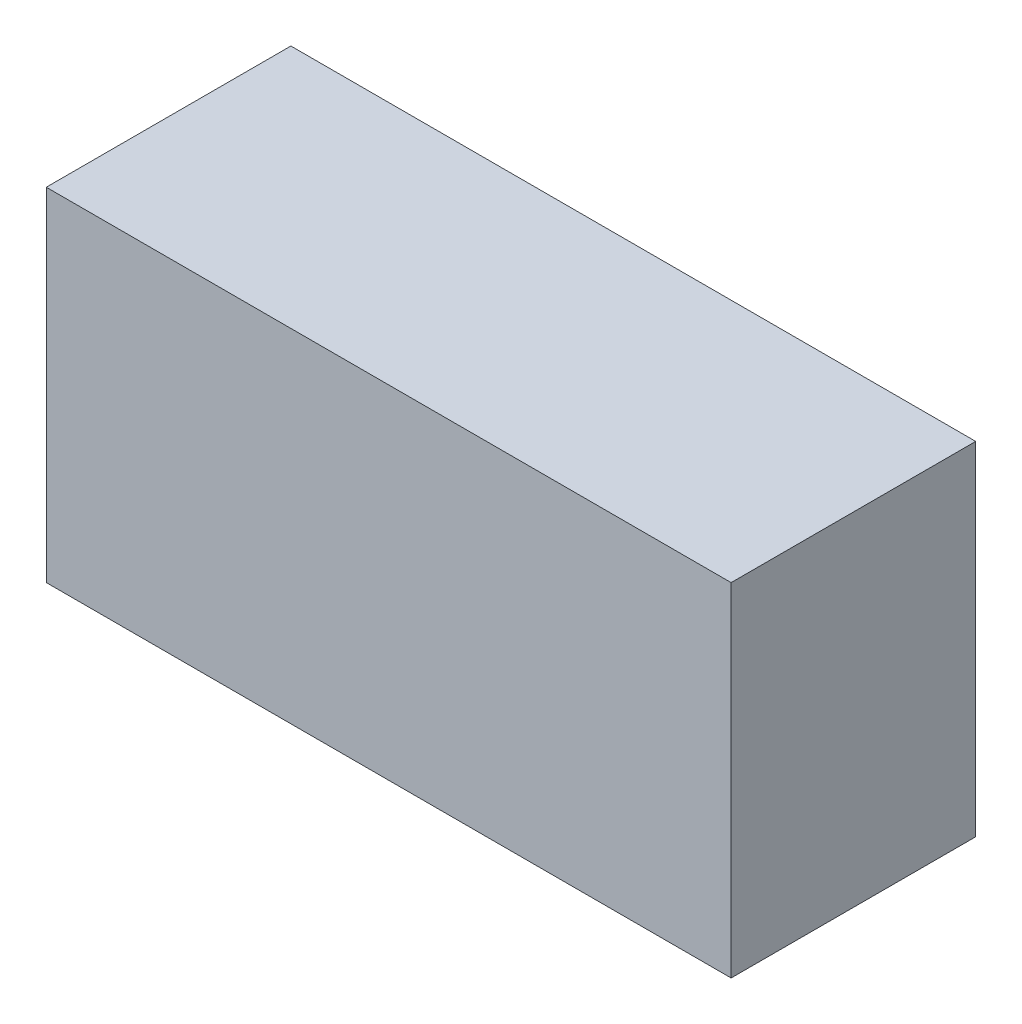
SolidWorks part; units mm, degrees
ref_plane "정면" through (0, 0, 0) normal (0, 0, 1) x (1, 0, 0)
ref_plane "윗면" through (0, 0, 0) normal (0, 1, 0) x (1, 0, 0)
ref_plane "우측면" through (0, 0, 0) normal (1, 0, 0) x (0, 0, -1)
sketch "스케치1" plane through (0, 0, 0) normal (0, 0, 1) x (1, 0, 0)
  line L1 (40.1645, 28.4375) -> (-29.8355, 28.4375)
  line L2 (40.1645, 28.4375) -> (40.1645, -6.5625)
  line L3 (40.1645, -6.5625) -> (-29.8355, -6.5625)
  line L4 (-29.8355, 28.4375) -> (-29.8355, -6.5625)
  dimension "D1" = 70
  dimension "D2" = 35
extrude "보스-돌출1" add sketch "스케치1" along normal blind 25
